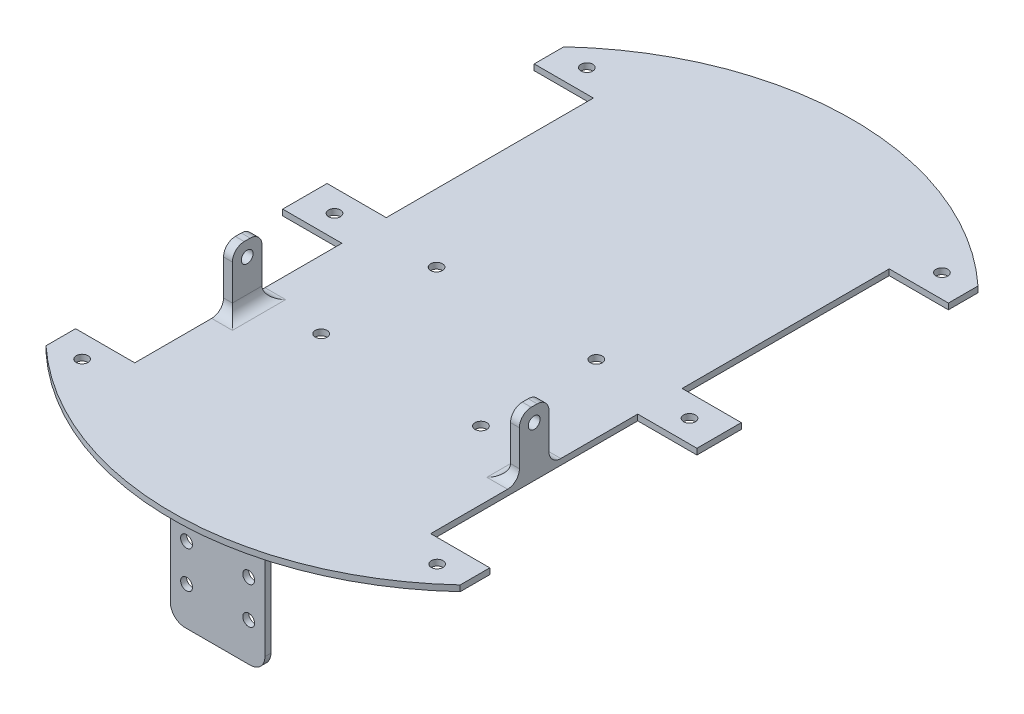
SolidWorks part; units mm, degrees
ref_plane "Front Plane" through (0, 0, 0) normal (0, 0, 1) x (1, 0, 0)
ref_plane "Top Plane" through (0, 0, 0) normal (0, 1, 0) x (1, 0, 0)
ref_plane "Right Plane" through (0, 0, 0) normal (1, 0, 0) x (0, 0, -1)
sketch "Sketch1" plane through (0, 0, 0) normal (0, 1, 0) x (1, 0, 0)
  line L0 (0, 125.021) -> (0, -215.1822) construction
  line L1 (70, 114.9547) -> (70, -215.1822) construction
  line L2 (-70, -236.6337) -> (-70, 93.8385) construction
  line L3 (-204.8663, -230) -> (265.7035, -230) construction
  line L4 (70, -27.5) -> (70, -37.5)
  line L5 (70, -37.5) -> (50, -37.5)
  line L6 (50, -37.5) -> (50, -107.5)
  line L7 (50, -107.5) -> (70, -107.5)
  line L8 (70, -107.5) -> (70, -122.5)
  line L9 (70, -122.5) -> (50, -122.5)
  line L10 (50, -122.5) -> (50, -192.5)
  line L11 (50, -192.5) -> (70, -192.5)
  line L12 (70, -192.5) -> (70, -202.5)
  line L13 (-70, -192.5) -> (-70, -202.5)
  line L14 (-50, -192.5) -> (-70, -192.5)
  line L15 (-50, -122.5) -> (-50, -192.5)
  line L16 (-70, -122.5) -> (-50, -122.5)
  line L17 (-70, -107.5) -> (-70, -122.5)
  line L18 (-50, -107.5) -> (-70, -107.5)
  line L19 (-50, -37.5) -> (-50, -107.5)
  line L20 (-70, -37.5) -> (-50, -37.5)
  line L21 (-70, -27.5) -> (-70, -37.5)
  arc A0 (-70, -27.5) -> (70, -27.5) centre (0, -102.8409) cw
  arc A1 (-70, -202.5) -> (70, -202.5) centre (0, -127.1591) ccw
  dimension "D8" = 10
  dimension "D1" = 230
  dimension "D2" = 70
  dimension "D3" = 70
  dimension "D4" = 70
  dimension "D5" = 70
  dimension "D6" = 15
  dimension "D7" = 37.5
  dimension "D9" = 20
extrude "Boss-Extrude1" add sketch "Sketch1" along normal blind 2
sketch "Sketch3" plane through (0, 2, 0) normal (0, 1, 0) x (1, 0, 0)
  line L1 (47, -162.5) -> (50, -162.5)
  line L2 (47, -162.5) -> (47, -152.5)
  line L3 (47, -152.5) -> (50, -152.5)
  line L4 (50, -162.5) -> (50, -152.5)
  line L5 (50, -192.5) -> (50, -122.5) construction
  line L6 (50, -157.5) -> (47, -157.5) construction
  line L7 (70, -192.5) -> (50, -192.5) construction
  line L8 (50, -122.5) -> (70, -122.5) construction
  dimension "D2" = 0
  dimension "D3" = 3
  dimension "D4" = 10
extrude "Boss-Extrude2" add sketch "Sketch3" along normal blind 20
sketch "Sketch4" plane through (47, 0, 0) normal (-1, 0, 0) x (0, 0, 1)
  line L0 (157.5, 22) -> (157.5, 2) construction
  line L1 (152.5, 22) -> (162.5, 22) construction
  line L2 (152.5, 2) -> (162.5, 2) construction
  circle A0 centre (157.5, 17) radius 2
  dimension "D2" = 4
  dimension "D1" = 15
extrude "Cut-Extrude2" cut sketch "Sketch4" against normal through all
fillet "Fillet1" radius 4 5 edges at (47, 2, 157.5) (48.5, 2, 162.5) (48.5, 2, 152.5) (48.5, 22, 152.5) (48.5, 22, 162.5)
mirror "Mirror1" about plane through (0, 0, 0) normal (1, 0, 0) of "Boss-Extrude2", "Fillet1", "Cut-Extrude2"
sketch "Sketch5" plane through (0, 2, 0) normal (0, 1, 0) x (1, 0, 0)
  line L0 (0, 0) -> (0, -241.5212) construction
  line L1 (-60, 12.4503) -> (-60, -241.5212) construction
  line L2 (-70, -107.5) -> (-70, -122.5) construction
  line L3 (-50, -107.5) -> (-70, -107.5) construction
  line L4 (-70, -37.5) -> (-50, -37.5) construction
  line L5 (-50, -192.5) -> (-70, -192.5) construction
  arc A0 (70, -27.5) -> (-70, -27.5) centre (0, -102.8409) ccw construction
  circle A1 centre (-60, -115) radius 2
  circle A2 centre (-60, -200.3) radius 2
  circle A3 centre (-60, -29.7) radius 2
  circle A4 centre (60, -200.3) radius 2
  circle A5 centre (60, -115) radius 2
  circle A6 centre (60, -29.7) radius 2
  dimension "D5" = 4
  dimension "D1" = 10
  dimension "D2" = 7.5
  dimension "D3" = 7.8
  dimension "D4" = 7.8
extrude "Cut-Extrude3" cut sketch "Sketch5" against normal through all
sketch "Sketch6" plane through (0, 0, 0) normal (0, -1, 0) x (1, 0, 0)
  line L0 (0, -49.7367) -> (0, 303.8037) construction
  line L1 (-27, 113.5) -> (27, 113.5) construction
  line L2 (-27, 113.5) -> (-27, 152.5) construction
  line L3 (-27, 152.5) -> (27, 152.5) construction
  line L4 (27, 113.5) -> (27, 152.5) construction
  line L5 (-70, 122.5) -> (-50, 122.5) construction
  circle A0 centre (-27, 152.5) radius 2
  circle A1 centre (27, 152.5) radius 2
  circle A2 centre (-27, 113.5) radius 2
  circle A3 centre (27, 113.5) radius 2
  circle A4 centre (-60, 115) radius 2 construction
  dimension "D1" = 39
  dimension "D2" = 54
  dimension "D3" = 30
extrude "Cut-Extrude4" cut sketch "Sketch6" against normal through all both and the other way through all
sketch "Sketch7" plane through (0, 0, 0) normal (0, -1, 0) x (1, 0, 0)
  line L0 (0, -66.3555) -> (0, 361.6978) construction
  line L1 (-93.4364, 212.5) -> (99.7954, 212.5) construction
  line L2 (70, 192.5) -> (50, 192.5) construction
  line L3 (-16, 212.5) -> (16, 212.5)
  line L4 (-16, 212.5) -> (-16, 214.5)
  line L5 (-16, 214.5) -> (16, 214.5)
  line L6 (16, 212.5) -> (16, 214.5)
  dimension "D1" = 2
  dimension "D2" = 32
  dimension "D3" = 20
extrude "Boss-Extrude3" add sketch "Sketch7" along normal blind 45
fillet "Fillet3" radius 5 4 edges at (16, -45, 213.5) (-16, -45, 213.5) (-16, 0, 213.5) (16, 0, 213.5)
fillet "Fillet4" radius 5 1 edges at (0, 0, 212.5)
sketch "Sketch8" plane through (0, 0, 214.5) normal (0, 0, 1) x (1, 0, 0)
  line L0 (0, 11.1142) -> (0, -46.0078) construction
  line L1 (-28.4977, -19.5) -> (34.4882, -19.5) construction
  line L2 (-26.2734, -32) -> (32.0618, -32) construction
  line L3 (-10.5, 10.0021) -> (-10.5, -46.0078) construction
  line L4 (10.5, 9.0922) -> (10.5, -44.2891) construction
  line L5 (11, -45) -> (-11, -45) construction
  circle A0 centre (-10.5, -19.5) radius 2
  circle A1 centre (10.5, -19.5) radius 2
  circle A2 centre (10.5, -32) radius 2
  circle A3 centre (-10.5, -32) radius 2
  dimension "D5" = 4
  dimension "D1" = 12.5
  dimension "D2" = 21
  dimension "D3" = 10.5
  dimension "D4" = 13
extrude "Cut-Extrude5" cut sketch "Sketch8" against normal through all
